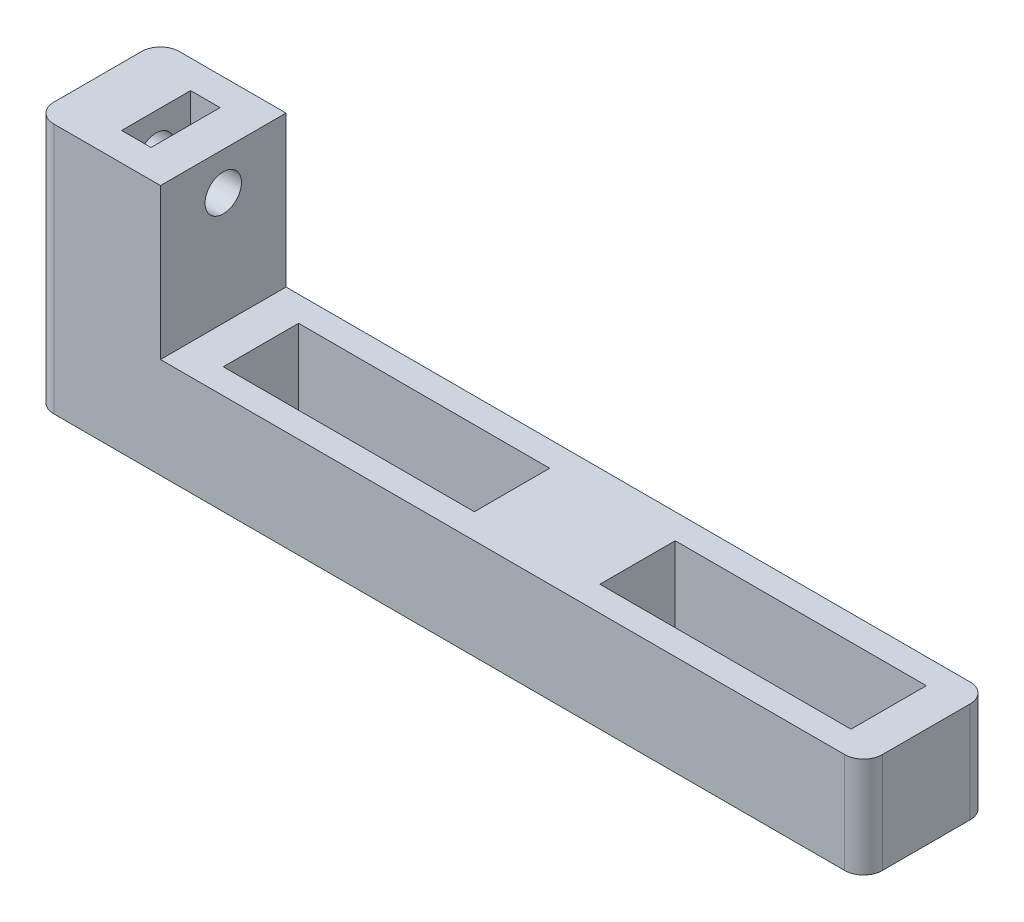
SolidWorks part; units mm, degrees
ref_plane "Alzado" through (0, 0, 0) normal (0, 0, 1) x (1, 0, 0)
ref_plane "Planta" through (0, 0, 0) normal (0, 1, 0) x (1, 0, 0)
ref_plane "Vista lateral" through (0, 0, 0) normal (1, 0, 0) x (0, 0, -1)
sketch "Croquis2" plane through (0, 0, 0) normal (0, 0, 1) x (1, 0, 0)
  line L0 (-160.3365, 23.5578) -> (-160.3365, 3.5578)
  line L1 (-160.3365, 3.5578) -> (-94.3365, 3.5578)
  line L2 (-94.3365, 3.5578) -> (-94.3365, 11.5578)
  line L3 (-94.3365, 11.5578) -> (-150.3365, 11.5578)
  line L4 (-150.3365, 11.5578) -> (-150.3365, 23.5578)
  line L5 (-150.3365, 23.5578) -> (-160.3365, 23.5578)
extrude "Saliente-Extruir1" add sketch "Croquis2" along normal blind 10
fillet "Redondeo5" radius 1.5 4 edges at (-94.3365, 7.5578, 0) (-94.3365, 7.5578, 10) (-160.3365, 13.5578, 0) (-160.3365, 13.5578, 10)
sketch "Croquis3" plane through (0, 11.5578, 0) normal (0, 1, 0) x (1, 0, 0)
  line L0 (-94.3365, -8.5) -> (-94.3365, -1.5) construction
  line L1 (-97.3365, -2) -> (-117.3365, -2)
  line L2 (-97.3365, -2) -> (-97.3365, -8)
  line L3 (-97.3365, -8) -> (-117.3365, -8)
  line L4 (-117.3365, -2) -> (-117.3365, -8)
  line L5 (-127.3365, -2) -> (-147.3365, -2)
  line L6 (-127.3365, -2) -> (-127.3365, -8)
  line L7 (-127.3365, -8) -> (-147.3365, -8)
  line L8 (-147.3365, -2) -> (-147.3365, -8)
  line L9 (-150.3365, -10) -> (-150.3365, 0) construction
  line L10 (-95.8365, -10) -> (-150.3365, -10) construction
  dimension "D1" = 6
  dimension "D2" = 6
  dimension "D3" = 3
  dimension "D4" = 20
  dimension "D5" = 3
  dimension "D6" = 20
  dimension "D7" = 2
  dimension "D8" = 2
extrude "Cortar-Extruir1" cut sketch "Croquis3" against normal blind 6.5
sketch "Croquis4" plane through (0, 5.0578, 0) normal (0, 1, 0) x (1, 0, 0)
  line L1 (-116.3365, -3.5) -> (-98.3365, -3.5)
  line L2 (-116.3365, -3.5) -> (-116.3365, -6.45)
  line L3 (-116.3365, -6.45) -> (-98.3365, -6.45)
  line L4 (-98.3365, -3.5) -> (-98.3365, -6.45)
  line L5 (-116.3365, -3.5) -> (-98.3365, -6.45) construction
  line L6 (-116.3365, -6.45) -> (-98.3365, -3.5) construction
  line L7 (-146.3365, -3.5) -> (-128.3365, -3.5)
  line L8 (-146.3365, -3.5) -> (-146.3365, -6.45)
  line L9 (-146.3365, -6.45) -> (-128.3365, -6.45)
  line L10 (-128.3365, -3.5) -> (-128.3365, -6.45)
  line L11 (-146.3365, -3.5) -> (-128.3365, -6.45) construction
  line L12 (-146.3365, -6.45) -> (-128.3365, -3.5) construction
  line L13 (-147.3365, -2) -> (-147.3365, -8) construction
  line L14 (-117.3365, -2) -> (-117.3365, -8) construction
  line L15 (-97.3365, -8) -> (-97.3365, -2) construction
  line L16 (-97.3365, -2) -> (-117.3365, -2) construction
  line L18 (-127.3365, -2) -> (-147.3365, -2) construction
  point P0 (-107.3365, -4.975)
  point P5 (-137.3365, -4.975)
  dimension "D1" = 18
  dimension "D2" = 1
  dimension "D3" = 1
  dimension "D4" = 1
  dimension "D5" = 1.5
  dimension "D6" = 2.95
  dimension "D7" = 2.95
  dimension "D8" = 1.5
extrude "Cortar-Extruir2" cut sketch "Croquis4" against normal up to vertex (1.5 mm away)
sketch "Croquis5" plane through (-150.3365, 0, 0) normal (1, 0, 0) x (0, 0, -1)
  line L0 (-10, 23.5578) -> (0, 23.5578) construction
  line L1 (-10, 11.5578) -> (-10, 23.5578) construction
  circle A0 centre (-5, 20.5578) radius 1.45
  dimension "D1" = 3
  dimension "D2" = 5
extrude "Cortar-Extruir3" cut sketch "Croquis5" against normal up to vertex (10 mm away)
sketch "Croquis6" plane through (0, 23.5578, 0) normal (0, 1, 0) x (1, 0, 0)
  line L0 (-150.3365, -10) -> (-158.8365, -10) construction
  line L1 (-153.3365, -2.25) -> (-155.6865, -2.25)
  line L2 (-153.3365, -2.25) -> (-153.3365, -7.75)
  line L3 (-153.3365, -7.75) -> (-155.6865, -7.75)
  line L4 (-155.6865, -2.25) -> (-155.6865, -7.75)
  line L6 (-150.3365, -10) -> (-150.3365, 0) construction
  dimension "D1" = 5.5
  dimension "D2" = 2.35
  dimension "D3" = 2.25
  dimension "D4" = 3
extrude "Cortar-Extruir4" cut sketch "Croquis6" against normal blind 6
